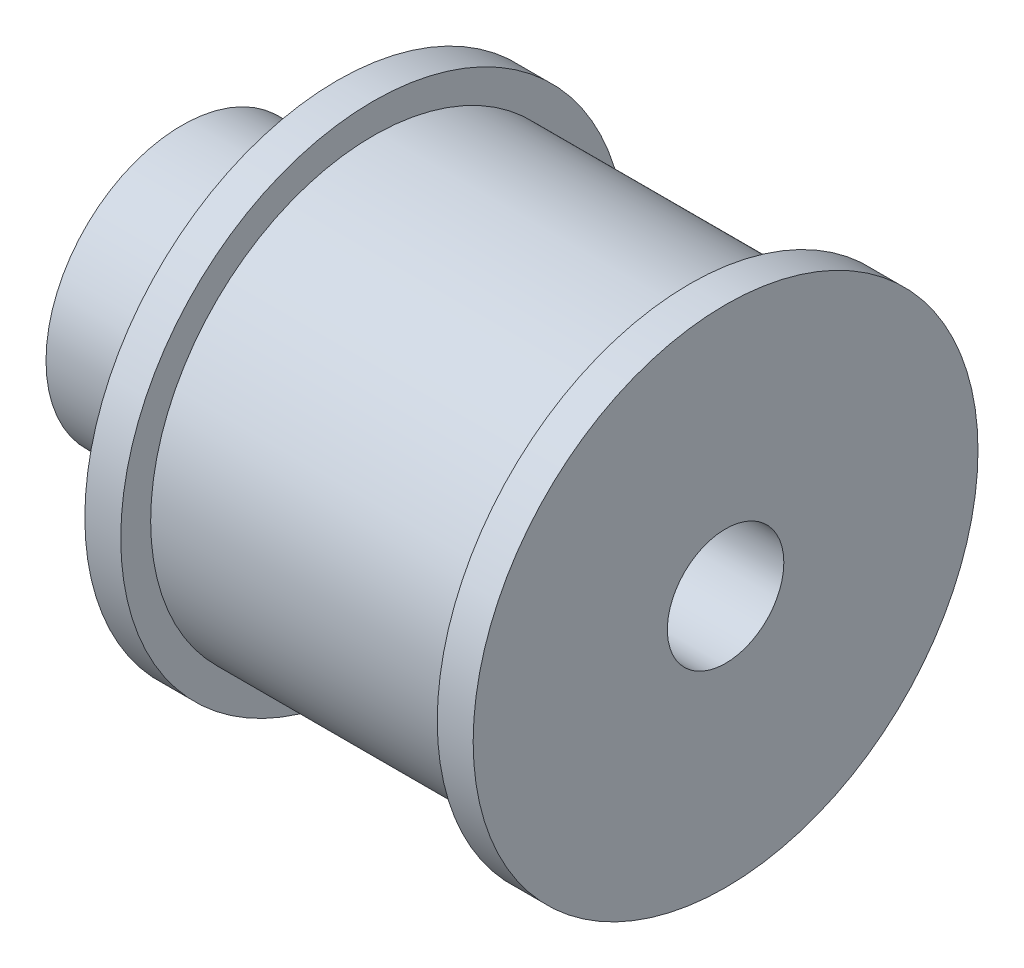
SolidWorks part; units mm, degrees
ref_plane "Front Plane" through (0, 0, 0) normal (0, 0, 1) x (1, 0, 0)
ref_plane "Top Plane" through (0, 0, 0) normal (0, 1, 0) x (1, 0, 0)
ref_plane "Right Plane" through (0, 0, 0) normal (1, 0, 0) x (0, 0, -1)
sketch "Sketch1" plane through (0, 0, 0) normal (0, 1, 0) x (1, 0, 0)
  line L0 (0, -11.46) -> (-8.15, -11.46)
  line L1 (-8.15, -13) -> (-10, -13)
  line L2 (-10, -13) -> (-10, -7)
  line L3 (10, 0) -> (10, -13)
  line L4 (10, -13) -> (8.15, -13)
  line L5 (8.15, -13) -> (8.15, -11.46)
  line L6 (8.15, -11.46) -> (0, -11.46)
  line L7 (-8.15, -11.46) -> (-8.15, -13)
  line L8 (-10, 0) -> (10, 0) construction
  line L9 (10, 0) -> (-10, 0)
  line L10 (-18, 0) -> (-18, -7)
  line L11 (-18, -7) -> (-10, -7)
  line L12 (-18, 0) -> (-10, 0)
  dimension "D1" = 13
  dimension "D2" = 1.85
  dimension "D3" = 10
  dimension "D4" = 11.46
  dimension "D5" = 10
  dimension "D6" = 1.85
  dimension "D7" = 7
  dimension "D8" = 8
revolve "Revolve1" add sketch "Sketch1" angle 360 about L8
hole_wizard "Ø6.0 (6) Diameter Hole2" positions "Sketch8" profile "Sketch7" hole size "Ø6.0" standard "ANSI Metric"
sketch "Sketch8" plane through (10, 0, 0) normal (1, 0, 0) x (0, 0, -1)
  point P0 (0, 0)
sketch "Sketch7" plane through (10, 0, 0) normal (0, 1, 0) x (0, 0, -1)
  line L0 (0, 0) -> (0, 25.8026)
  line L1 (0, 25.8026) -> (3, 24)
  line L2 (3, 24) -> (3, 0)
  line L5 (3, 0) -> (0, 0)
  line L10 (0, 25.8026) -> (-3, 24) construction
  line L11 (0, -6.35) -> (0, 107.95) construction
  dimension "Hole Dia." = 6
  dimension "Hole Depth" = 24
  dimension "Drill Angle" = 118
